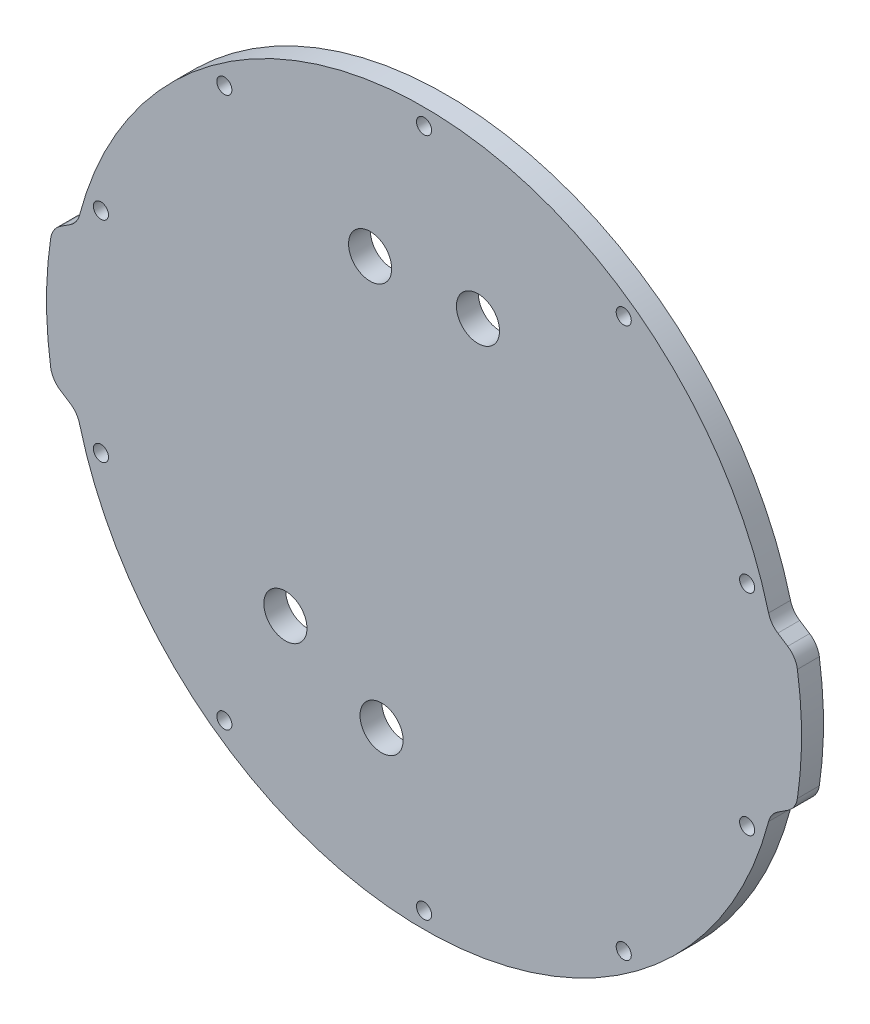
SolidWorks part; units mm, degrees
other "Markup1"
sketch "Sketch2" plane through (-87.5, -82.55, 2.54) normal (0, 0, 1) x (1, 0, 0)
material "6061 Alloy"
ref_plane "Front Plane" through (0, 0, 0) normal (0, 0, 1) x (1, 0, 0)
ref_plane "Top Plane" through (0, 0, 0) normal (0, 1, 0) x (1, 0, 0)
ref_plane "Right Plane" through (0, 0, 0) normal (1, 0, 0) x (0, 0, -1)
sketch "Sketch1" plane through (0, 0, 0) normal (0, 0, 1) x (1, 0, 0)
  line L0 (-87.5, 0) -> (87.5, 0) construction
  line L1 (0, -87.5) -> (0, 87.5) construction
  line L2 (-86.1626, 15.24) -> (-80.3219, 19.05)
  line L3 (86.1626, 15.24) -> (80.3219, 19.05)
  line L4 (-86.1626, -15.24) -> (-80.3219, -19.05)
  line L5 (86.1626, -15.24) -> (80.3219, -19.05)
  line L6 (-44.5, 30.3438) -> (-43.5, 30.3438) construction
  line L7 (-43.5, -19.6562) -> (43.5, -19.6562) construction
  line L8 (-43.5, -19.6562) -> (-43.5, 30.3438) construction
  line L9 (-43.5, 30.3438) -> (43.5, 30.3438) construction
  line L10 (43.5, -19.6562) -> (43.5, 30.3438) construction
  line L11 (-43.5, -19.6562) -> (43.5, 30.3438) construction
  line L12 (-43.5, 30.3438) -> (43.5, -19.6562) construction
  line L13 (-44.5, 31.3438) -> (44.5, 31.3438) construction
  line L14 (-44.5, 31.3438) -> (-44.5, -20.6562) construction
  line L15 (-44.5, -20.6562) -> (44.5, -20.6562) construction
  line L16 (44.5, 31.3438) -> (44.5, -20.6562) construction
  line L17 (-43.5, 30.3438) -> (-43.5, 31.3438) construction
  line L18 (43.5, -19.6562) -> (43.5, -20.6562) construction
  line L20 (44.5, -19.6562) -> (43.5, -19.6562) construction
  arc A0 (-86.1626, 15.24) -> (-86.1626, -15.24) centre (0, 0) ccw
  arc A1 (-80.3219, 19.05) -> (-80.3219, -19.05) centre (0, 0) ccw construction
  circle A2 centre (0, 0) radius 78.74 construction
  circle A5 centre (0, 78.74) radius 1.75
  circle A10 centre (46.2822, 63.702) radius 1.75
  circle A11 centre (74.8862, 24.332) radius 1.75
  circle A12 centre (74.8862, -24.332) radius 1.75
  circle A13 centre (46.2822, -63.702) radius 1.75
  circle A14 centre (0, -78.74) radius 1.75
  circle A15 centre (-46.2822, -63.702) radius 1.75
  circle A16 centre (-74.8862, -24.332) radius 1.75
  circle A17 centre (-74.8862, 24.332) radius 1.75
  circle A18 centre (-46.2822, 63.702) radius 1.75
  arc A19 (86.1626, 15.24) -> (-86.1626, 15.24) centre (0, 0) ccw construction
  arc A20 (86.1626, -15.24) -> (86.1626, 15.24) centre (0, 0) ccw
  arc A21 (-86.1626, -15.24) -> (86.1626, -15.24) centre (0, 0) ccw construction
  arc A22 (80.3219, 19.05) -> (-80.3219, 19.05) centre (0, 0) ccw
  arc A23 (80.3219, -19.05) -> (80.3219, 19.05) centre (0, 0) ccw construction
  arc A24 (-80.3219, -19.05) -> (80.3219, -19.05) centre (0, 0) ccw
  circle A26 centre (-12.5, 46.3438) radius 10 construction
  circle A27 centre (12.5, 46.3438) radius 10 construction
  circle A31 centre (0, 0) radius 63 construction
  circle A32 centre (-12.5, 46.3438) radius 15 construction
  circle A33 centre (-9.846, -46.9793) radius 10 construction
  circle A34 centre (-32.1347, -35.6562) radius 10 construction
  circle A35 centre (-9.846, -46.9793) radius 15 construction
  circle A36 centre (-32.1347, -35.6562) radius 15 construction
  circle A38 centre (-32.1347, -35.6562) radius 5
  circle A39 centre (-9.846, -46.9793) radius 5
  circle A40 centre (-12.5, 46.3438) radius 5
  circle A41 centre (12.5, 46.3438) radius 5
  point P0 (0, 5.3438)
  dimension "D2" = 157.48
  dimension "D3" = 165.1
  dimension "D4" = 175
  dimension "D5" = 3.5
  dimension "D6" = 50
  dimension "D7" = 87
  dimension "D12" = 20
  dimension "D13" = 126
  dimension "D14" = 5
  dimension "D17" = 10
  dimension "D9" = 19.05
  dimension "D10" = 15.24
  dimension "D11" = 1
  dimension "D8" = 10
extrude "Boss-Extrude1" add sketch "Sketch1" along normal mid plane 5.08
fillet "Fillet1" radius 5.08 8 edges at (-86.1626, 15.24, 0) (-80.3219, 19.05, 0) (-86.1626, -15.24, 0) (-80.3219, -19.05, 0) (86.1626, -15.24, 0) (80.3219, -19.05, 0) (86.1626, 15.24, 0) (80.3219, 19.05, 0)
